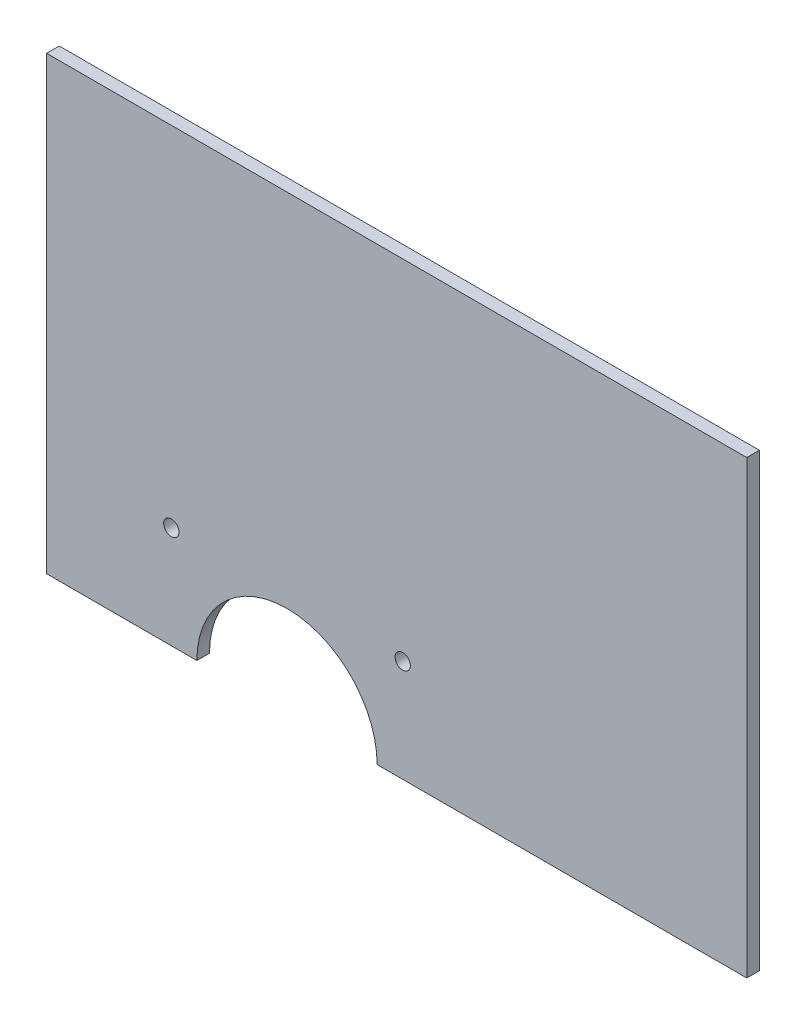
SolidWorks part; units mm, degrees
ref_plane "Plan de face" through (0, 0, 0) normal (0, 0, 1) x (1, 0, 0)
ref_plane "Plan de dessus" through (0, 0, 0) normal (0, 1, 0) x (1, 0, 0)
ref_plane "Plan de droite" through (0, 0, 0) normal (1, 0, 0) x (0, 0, -1)
sketch "Esquisse1" plane through (0, 0, 0) normal (0, 0, 1) x (1, 0, 0)
  line L1 (-119.563, 68.7323) -> (113.437, 68.7323)
  line L2 (-119.563, 68.7323) -> (-119.563, -81.2677)
  line L3 (-119.563, -81.2677) -> (113.437, -81.2677)
  line L4 (113.437, 68.7323) -> (113.437, -81.2677)
  dimension "D1" = 233
  dimension "D2" = 150
extrude "Boss.-Extru.1" add sketch "Esquisse1" along normal blind 4.2
sketch "Esquisse2" plane through (0, 0, 4.2) normal (0, 0, 1) x (1, 0, 0)
  line L0 (-69.563, -81.2677) -> (-9.563, -81.2677)
  line L2 (-119.563, -81.2677) -> (113.437, -81.2677) construction
  arc A1 (-69.563, -81.2677) -> (-9.563, -81.2677) centre (-39.563, -81.2677) cw
  circle A2 centre (-78.063, -47.2677) radius 2.55
  circle A3 centre (-1.063, -47.2677) radius 2.55
  dimension "D2" = 30
  dimension "D4" = 5.1
  dimension "D5" = 5.1
  dimension "D1" = 50
  dimension "D3" = 0
  dimension "D6" = 34
  dimension "D7" = 0
  dimension "D8" = 77
  dimension "D9" = 38.5
extrude "Enlèv. mat.-Extru.1" cut sketch "Esquisse2" against normal through all
